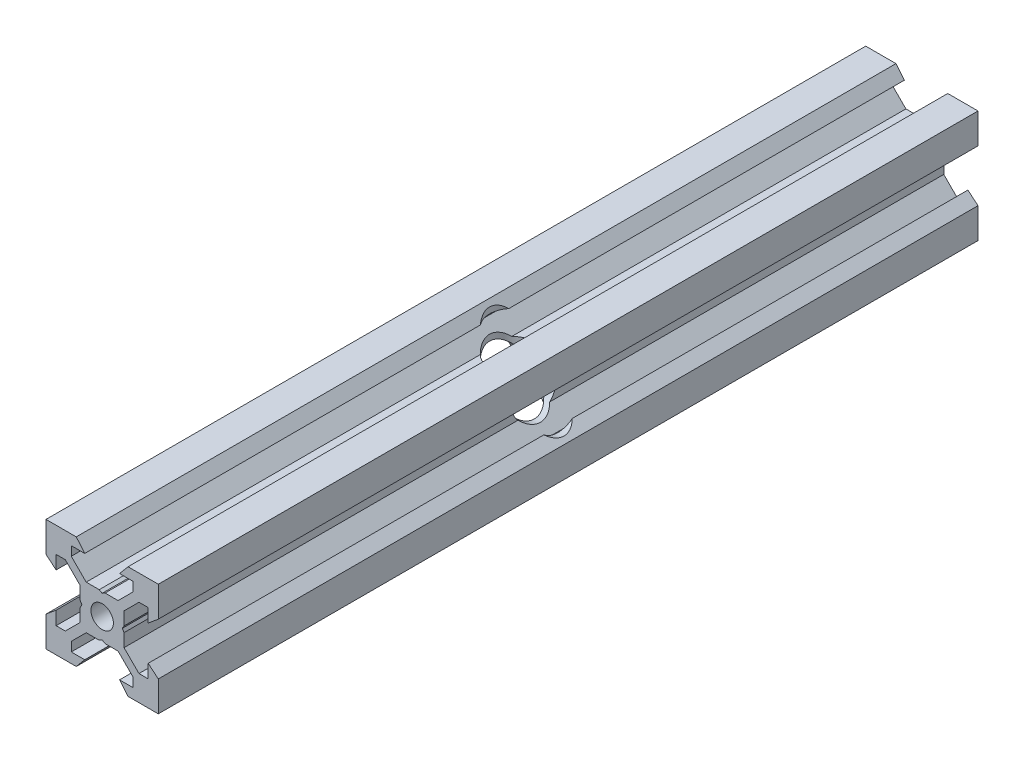
SolidWorks part; units mm, degrees
material "3.3535 (EN-AW 5754)"
ref_plane "Front Plane" through (0, 0, 0) normal (0, 0, 1) x (1, 0, 0)
ref_plane "Top Plane" through (0, 0, 0) normal (0, 1, 0) x (1, 0, 0)
ref_plane "Right Plane" through (0, 0, 0) normal (1, 0, 0) x (0, 0, -1)
sketch "Sketch1" plane through (0, 0, 0) normal (0, 0, 1) x (1, 0, 0)
  line L0 (10, 10) -> (4.6104, 10) construction
  line L1 (10, 10) -> (10, 4.6104) construction
  line L2 (10, -10) -> (10, -4.6104) construction
  line L3 (10, -10) -> (4.6104, -10) construction
  line L4 (10, 10) -> (10, 4.6104)
  line L5 (6.5607, 5.5) -> (8.2, 5.5)
  line L6 (5.5, 8.2) -> (5.5, 6.5607)
  line L7 (10, 10) -> (4.6104, 10)
  line L8 (10, 10) -> (10, 4.6104)
  line L9 (6.5607, 5.5) -> (3.9, 2.8393)
  line L10 (5.5, 6.5607) -> (2.8393, 3.9)
  line L11 (10, 4.6104) -> (8.2, 3.1)
  line L12 (4.6104, 10) -> (3.1, 8.2)
  line L13 (8.2, 3.1) -> (8.2, 5.5)
  line L14 (3.1, 8.2) -> (5.5, 8.2)
  line L15 (-6.5607, 5.5) -> (-8.2, 5.5)
  line L16 (6.5607, -5.5) -> (8.2, -5.5)
  line L17 (3.1, -8.2) -> (5.5, -8.2)
  line L18 (8.2, -3.1) -> (8.2, -5.5)
  line L19 (4.6104, -10) -> (3.1, -8.2)
  line L20 (10, -4.6104) -> (8.2, -3.1)
  line L21 (0.5196, -3.9) -> (0, -3.6)
  line L22 (0.5196, 3.9) -> (0, 3.6)
  line L23 (3.6, 0) -> (3.9, -0.5196)
  line L24 (3.9, 0.5196) -> (3.6, 0)
  line L25 (3.9, 0.5196) -> (3.9, 2.8393)
  line L26 (2.8393, 3.9) -> (0.5196, 3.9)
  line L27 (3.9, -2.8393) -> (3.9, -0.5196)
  line L28 (2.8393, -3.9) -> (0.5196, -3.9)
  line L29 (5.5, -6.5607) -> (2.8393, -3.9)
  line L30 (6.5607, -5.5) -> (3.9, -2.8393)
  line L31 (10, -10) -> (10, -4.6104)
  line L32 (10, -10) -> (4.6104, -10)
  line L33 (5.5, -8.2) -> (5.5, -6.5607)
  line L34 (-6.5607, -5.5) -> (-8.2, -5.5)
  line L35 (10, -10) -> (10, -4.6104)
  line L36 (0, 0) -> (0, 8.2) construction
  line L37 (-10, -10) -> (-4.6104, -10) construction
  line L38 (-10, -10) -> (-10, -4.6104) construction
  line L39 (-10, 10) -> (-10, 4.6104) construction
  line L40 (-10, 10) -> (-4.6104, 10) construction
  line L41 (-10, -10) -> (-10, -4.6104)
  line L43 (-5.5, -8.2) -> (-5.5, -6.5607)
  line L44 (-10, -10) -> (-4.6104, -10)
  line L45 (-10, -10) -> (-10, -4.6104)
  line L46 (-6.5607, -5.5) -> (-3.9, -2.8393)
  line L47 (-5.5, -6.5607) -> (-2.8393, -3.9)
  line L48 (-2.8393, -3.9) -> (-0.5196, -3.9)
  line L49 (-3.9, -2.8393) -> (-3.9, -0.5196)
  line L50 (-2.8393, 3.9) -> (-0.5196, 3.9)
  line L51 (-3.9, 0.5196) -> (-3.9, 2.8393)
  line L52 (-3.9, 0.5196) -> (-3.6, 0)
  line L53 (-3.6, 0) -> (-3.9, -0.5196)
  line L54 (-0.5196, 3.9) -> (0, 3.6)
  line L55 (-0.5196, -3.9) -> (0, -3.6)
  line L56 (-10, -4.6104) -> (-8.2, -3.1)
  line L57 (-4.6104, -10) -> (-3.1, -8.2)
  line L58 (-8.2, -3.1) -> (-8.2, -5.5)
  line L59 (-3.1, -8.2) -> (-5.5, -8.2)
  line L60 (-10, -10) -> (10, -10) construction
  line L61 (-10, -10) -> (-10, 10) construction
  line L62 (-3.1, 8.2) -> (-5.5, 8.2)
  line L63 (-8.2, 3.1) -> (-8.2, 5.5)
  line L64 (-4.6104, 10) -> (-3.1, 8.2)
  line L65 (-10, 4.6104) -> (-8.2, 3.1)
  line L66 (-5.5, 6.5607) -> (-2.8393, 3.9)
  line L67 (-6.5607, 5.5) -> (-3.9, 2.8393)
  line L68 (-10, 10) -> (-10, 4.6104)
  line L69 (-10, 10) -> (-4.6104, 10)
  line L70 (-5.5, 8.2) -> (-5.5, 6.5607)
  line L71 (-10, 10) -> (10, 10) construction
  line L72 (-10, 10) -> (-10, 4.6104)
  line L73 (10, -10) -> (10, 10) construction
  line L74 (-10, -10) -> (10, 10) construction
  line L75 (-10, 10) -> (10, -10) construction
  circle A0 centre (0, 0) radius 2
  dimension "D7" = 4
  dimension "D1" = 20
  dimension "D2" = 5.3896
  dimension "D3" = 4.5
  dimension "D4" = 50
  dimension "D5" = 1.8
  dimension "D6" = 1.5104
  dimension "D8" = 5.5
  dimension "D9" = 120
  dimension "D10" = 0.3
  dimension "D11" = 2.3197
  dimension "D12" = 7.8
  dimension "D13" = 7.8
  dimension "D14" = 1.5
  dimension "D15" = 2.6607
extrude "Boss-Extrude1" add sketch "Sketch1" along normal blind 146 contours L70 L62 L64 L69 L68 L65 L63 L15 L67 L51 L52 L53 L49 L46 L34 L58 L56 L41 L44 L57 L59 L43 L47 L48 L55 L21 L28 L29 L33 L17 L19 L32 L31 L20 L18 L16 L30 L27 L23 L24 L25 L9 L5 L13 L11 L4 L7 L12 L14 L6 L10
sketch "Sketch4" plane through (0, 0, 0) normal (1, 0, 0) x (0, 0, -1)
  line L0 (-146, 0) -> (0, 0) construction
  circle A0 centre (-73, 0) radius 4
  dimension "D1" = 8
extrude "Cut-Extrude1" cut sketch "Sketch4" against normal through all both and the other way through all
sketch "Sketch5" plane through (0, 0, 0) normal (0, 1, 0) x (1, 0, 0)
  line L0 (0, 0) -> (0, -146) construction
  circle A0 centre (0, -73) radius 4
  dimension "D1" = 8
extrude "Cut-Extrude2" cut sketch "Sketch5" against normal through all both and the other way through all
